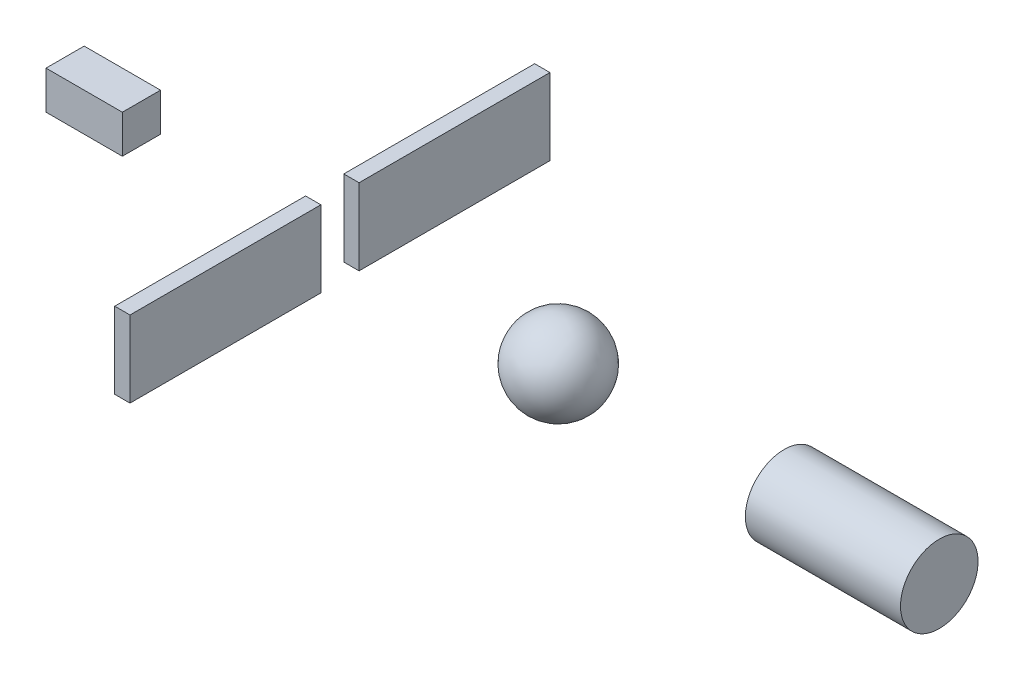
SolidWorks part; units mm, degrees
ref_plane "Front Plane" through (0, 0, 0) normal (0, 0, 1) x (1, 0, 0)
ref_plane "Top Plane" through (0, 0, 0) normal (0, 1, 0) x (1, 0, 0)
ref_plane "Right Plane" through (0, 0, 0) normal (1, 0, 0) x (0, 0, -1)
sketch "Sketch2" plane through (0, 0, 0) normal (0, 0, 1) x (1, 0, 0)
  line L0 (0, 0) -> (50, 0) construction
  line L1 (-350, -25) -> (-250, -25)
  line L2 (-350, -25) -> (-350, 25)
  line L3 (-350, 25) -> (-250, 25)
  line L4 (-250, -25) -> (-250, 25)
  line L5 (-350, -25) -> (-250, 25) construction
  line L6 (-350, 25) -> (-250, -25) construction
  point P0 (-300, 0)
  dimension "D1" = 50
  dimension "D2" = 100
  dimension "D3" = 250
  dimension "D4" = 50
extrude "Boss-Extrude2" add sketch "Sketch2" along normal mid plane 50
sketch "Sketch3" plane through (0, 0, 0) normal (0, 1, 0) x (1, 0, 0)
  line L0 (0, 0) -> (794.9, 0) construction
  line L1 (240, 0) -> (351.7, 0)
  line L3 (591.7, 0) -> (794.9, 0)
  line L4 (591.7, 0) -> (591.7, 50.8)
  line L5 (591.7, 50.8) -> (794.9, 50.8)
  line L6 (794.9, 0) -> (794.9, 50.8)
  arc A0 (240, 0) -> (351.7, 0) centre (295.85, 0) cw
  dimension "D1" = 55.85
  dimension "D2" = 295.85
  dimension "D3" = 50.8
  dimension "D4" = 203.2
  dimension "D5" = 295.85
revolve "Revolve1" add sketch "Sketch3" angle 360 about L0
sketch "Sketch4" plane through (0, 0, 0) normal (0, 1, 0) x (1, 0, 0)
  line L0 (0, 0) -> (91.7941, 0) construction
  line L1 (10, 275) -> (-10, 275)
  line L2 (10, 275) -> (10, 25)
  line L3 (10, 25) -> (-10, 25)
  line L4 (-10, 275) -> (-10, 25)
  line L5 (10, 275) -> (-10, 25) construction
  line L6 (10, 25) -> (-10, 275) construction
  line L7 (10, -25) -> (-10, -275) construction
  line L8 (10, -275) -> (-10, -25) construction
  line L9 (-10, -275) -> (-10, -25)
  line L10 (10, -25) -> (-10, -25)
  line L11 (10, -275) -> (10, -25)
  line L12 (10, -275) -> (-10, -275)
  point P0 (0, 150)
  point P12 (0, -150)
  dimension "D1" = 20
  dimension "D2" = 250
  dimension "D3" = 25
extrude "Boss-Extrude3" add sketch "Sketch4" along normal mid plane 100 separate body
